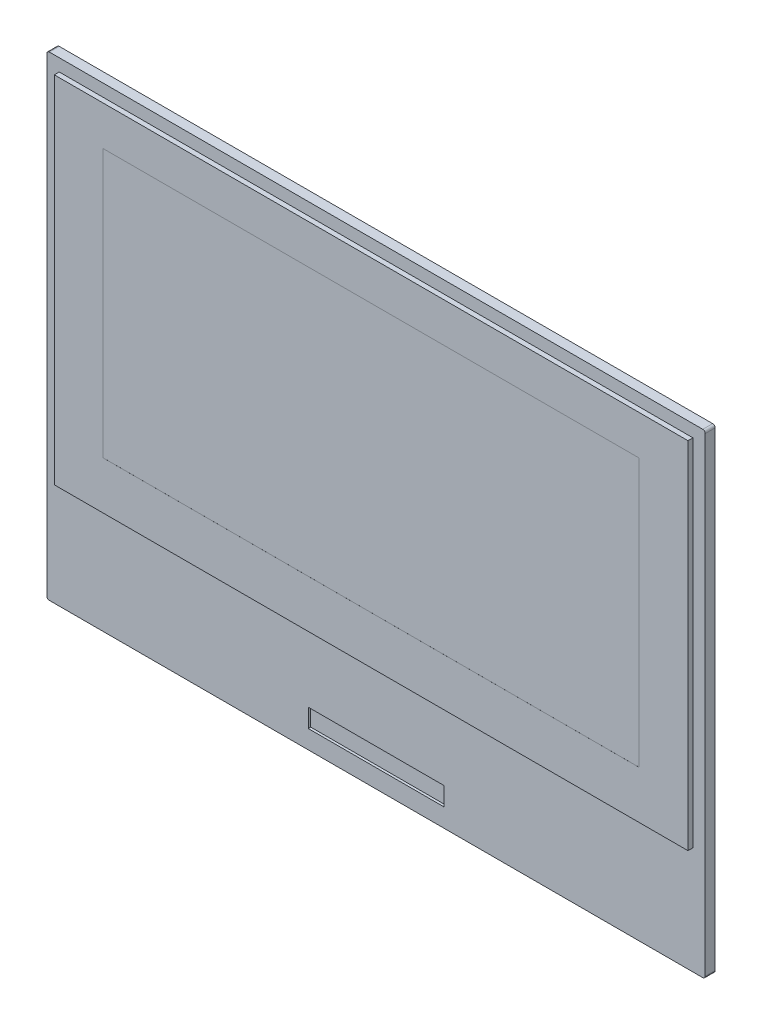
SolidWorks part; units mm, degrees
ref_plane "Front Plane" through (0, 0, 0) normal (0, 0, 1) x (1, 0, 0)
ref_plane "Top Plane" through (0, 0, 0) normal (0, 1, 0) x (1, 0, 0)
ref_plane "Right Plane" through (0, 0, 0) normal (1, 0, 0) x (0, 0, -1)
sketch "Sketch3" plane through (0, 0, 0) normal (0, 0, 1) x (1, 0, 0)
  line L1 (-13.35, 9.63) -> (13.35, 9.63)
  line L2 (-13.35, 9.63) -> (-13.35, -9.63)
  line L3 (-13.35, -9.63) -> (13.35, -9.63)
  line L4 (13.35, 9.63) -> (13.35, -9.63)
  line L5 (-13.35, 9.63) -> (13.35, -9.63) construction
  line L6 (-13.35, -9.63) -> (13.35, 9.63) construction
  point P0 (0, 0)
  dimension "D1" = 26.7
  dimension "D2" = 19.26
extrude "Boss-Extrude1" add sketch "Sketch3" against normal blind 0.4
sketch "Sketch5" plane through (0, 0, 0) normal (0, 0, 1) x (1, 0, 0)
  line L0 (13.35, 9.63) -> (-13.35, 9.63) construction
  line L1 (-12.85, 9.13) -> (12.85, 9.13)
  line L2 (-12.85, 9.13) -> (-12.85, -5.27)
  line L3 (-12.85, -5.27) -> (12.85, -5.27)
  line L4 (12.85, 9.13) -> (12.85, -5.27)
  line L5 (13.35, -9.63) -> (13.35, 9.63) construction
  line L6 (-13.35, 9.63) -> (-13.35, -9.63) construction
  dimension "D1" = 0.5
  dimension "D2" = 14.4
  dimension "D3" = 0.5
  dimension "D4" = 0.5
extrude "Boss-Extrude3" add sketch "Sketch5" along normal blind 0.2
sketch "Sketch6" plane through (0, 0, 0.2) normal (0, 0, 1) x (1, 0, 0)
  line L0 (-13.35, 9.63) -> (-13.35, -9.63) construction
  line L1 (-10.872, 7.53) -> (10.872, 7.53)
  line L2 (-10.872, 7.53) -> (-10.872, -3.334)
  line L3 (-10.872, -3.334) -> (10.872, -3.334)
  line L4 (10.872, 7.53) -> (10.872, -3.334)
  line L5 (13.35, -9.63) -> (13.35, 9.63) construction
  line L6 (13.35, 9.63) -> (-13.35, 9.63) construction
  dimension "D1" = 2.478
  dimension "D2" = 2.478
  dimension "D3" = 2.1
  dimension "D4" = 10.864
extrude "Cut-Extrude1" cut sketch "Sketch6" against normal blind 0.001
fillet "Fillet1" radius 0.1 4 edges at (13.35, -9.63, -0.2) (-13.35, -9.63, -0.2) (-13.35, 9.63, -0.2) (13.35, 9.63, -0.2)
sketch "Sketch7" plane through (0, 0, 0) normal (0, 0, 1) x (1, 0, 0)
  line L0 (0, -12.4526) -> (0, 13.7464) construction
  line L1 (-13.25, -9.63) -> (13.25, -9.63) construction
  line L2 (-2.75, -8.13) -> (2.75, -8.13)
  line L3 (-2.75, -8.13) -> (-2.75, -8.88)
  line L4 (-2.75, -8.88) -> (2.75, -8.88)
  line L5 (2.75, -8.13) -> (2.75, -8.88)
  line L6 (-2.75, -8.13) -> (2.75, -8.88) construction
  line L7 (-2.75, -8.88) -> (2.75, -8.13) construction
  point P3 (0, -8.505)
  dimension "D1" = 0.75
  dimension "D2" = 5.5
  dimension "D3" = 0.75
  dimension "D4" = 0.75
extrude "Cut-Extrude2" cut sketch "Sketch7" against normal blind 0.1
sketch "Sketch8" plane through (0, 0, -0.4) normal (0, 0, -1) x (-1, 0, 0)
  line L0 (0, 11.9998) -> (0, -12.582) construction
  line L1 (13.25, -9.63) -> (-13.25, -9.63) construction
  line L2 (-2.75, -8.13) -> (2.75, -8.13)
  line L3 (-2.75, -8.13) -> (-2.75, -8.88)
  line L4 (-2.75, -8.88) -> (2.75, -8.88)
  line L5 (2.75, -8.13) -> (2.75, -8.88)
  line L6 (-2.75, -8.13) -> (2.75, -8.88) construction
  line L7 (-2.75, -8.88) -> (2.75, -8.13) construction
  point P3 (0, -8.505)
  dimension "D1" = 0.75
  dimension "D2" = 0.75
  dimension "D3" = 5.5
extrude "Cut-Extrude3" cut sketch "Sketch8" against normal blind 0.1
